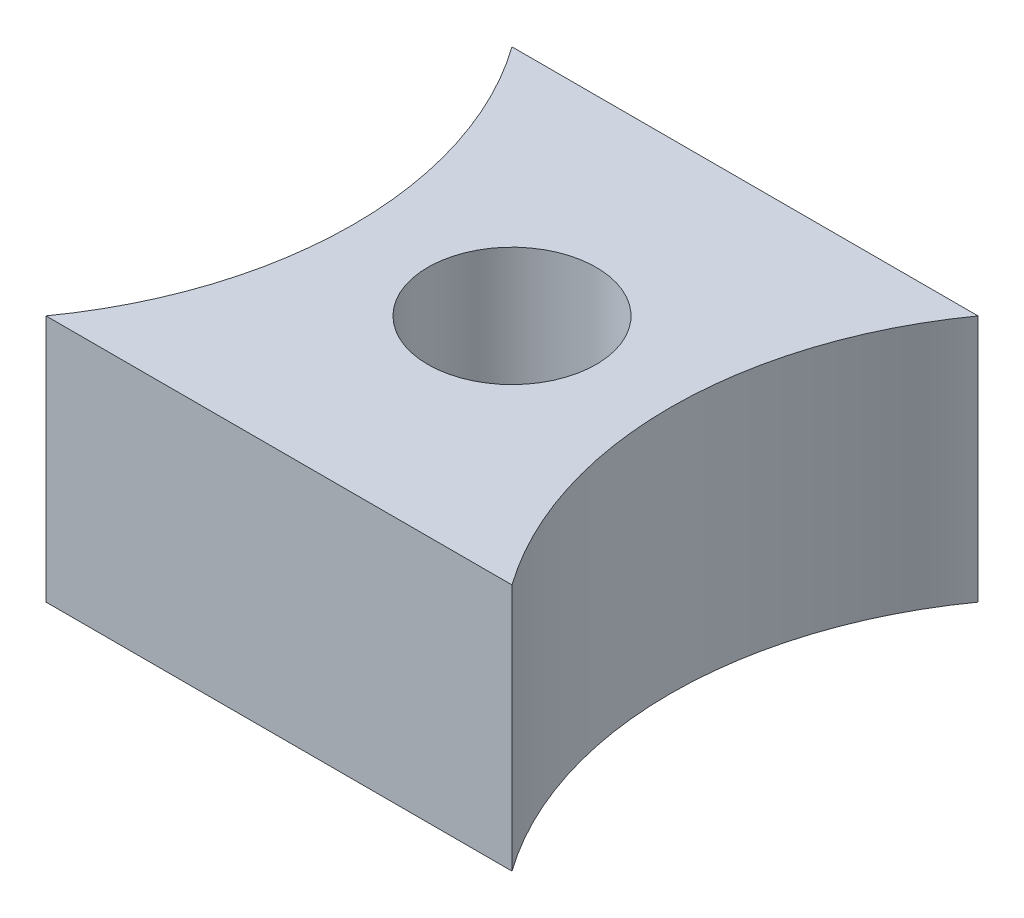
SolidWorks part; units mm, degrees
material "3003 Alloy"
ref_plane "Front Plane" through (0, 0, 0) normal (0, 0, 1) x (1, 0, 0)
ref_plane "Top Plane" through (0, 0, 0) normal (0, 1, 0) x (1, 0, 0)
ref_plane "Right Plane" through (0, 0, 0) normal (1, 0, 0) x (0, 0, -1)
sketch "Sketch1" plane through (0, 0, 0) normal (0, 1, 0) x (1, 0, 0)
  line L0 (0, 5.95) -> (0, -5.95) construction
  line L1 (-5.95, -5.95) -> (5.95, -5.95)
  line L3 (-5.95, 5.95) -> (5.95, 5.95)
  line L5 (-5.95, -5.95) -> (5.95, 5.95) construction
  line L6 (-5.95, 5.95) -> (5.95, -5.95) construction
  arc A0 (-5.95, -5.95) -> (-5.95, 5.95) centre (-14.2963, 0) ccw
  arc A1 (5.95, -5.95) -> (5.95, 5.95) centre (14.2963, 0) cw
  point P0 (0, 0)
  point P6 (0, 0)
  point P11 (0, 0)
  point P12 (-25.0384, 0.2218)
  dimension "D2" = 20.5
  dimension "D3" = 10.25
  dimension "D1" = 11.9
  dimension "D4" = 5.95
extrude "Boss-Extrude1" add sketch "Sketch1" against normal blind 6.33
sketch "Sketch2" plane through (0, 0, 0) normal (0, 1, 0) x (1, 0, 0)
  circle A0 centre (0, 0) radius 2.15
  dimension "D1" = 4.3
extrude "Cut-Extrude1" cut sketch "Sketch2" against normal through all contours A0
